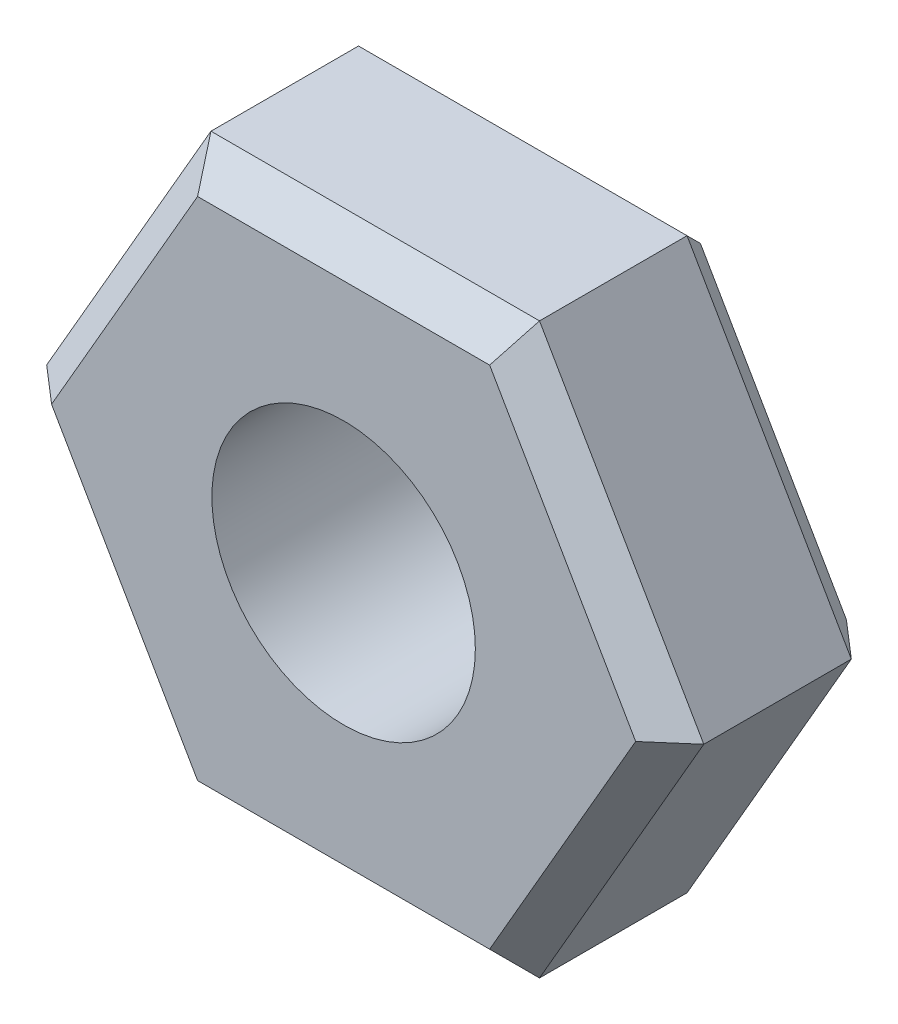
SolidWorks part; units mm, degrees
ref_plane "Front Plane" through (0, 0, 0) normal (0, 0, 1) x (1, 0, 0)
ref_plane "Top Plane" through (0, 0, 0) normal (0, 1, 0) x (1, 0, 0)
ref_plane "Right Plane" through (0, 0, 0) normal (1, 0, 0) x (0, 0, -1)
sketch "Sketch1" plane through (0, 0, 0) normal (0, 0, 1) x (1, 0, 0)
  line L1 (3.1177, 0) -> (1.5588, 2.7)
  line L2 (1.5588, 2.7) -> (-1.5588, 2.7)
  line L3 (-1.5588, 2.7) -> (-3.1177, 0)
  line L4 (-3.1177, 0) -> (-1.5588, -2.7)
  line L5 (-1.5588, -2.7) -> (1.5588, -2.7)
  line L6 (1.5588, -2.7) -> (3.1177, 0)
  circle A0 centre (0, 0) radius 2.7 construction
  circle A1 centre (0, 0) radius 1.25
  dimension "D1" = 5.4
  dimension "D2" = 2.5
extrude "Boss-Extrude1" add sketch "Sketch1" along normal mid plane 2
chamfer "Chamfer1" distance 0.3 angle 45 12 edges at (2.3383, 1.35, -1) (2.3383, -1.35, -1) (0, -2.7, -1) (-2.3383, -1.35, -1) (-2.3383, 1.35, -1) (0, 2.7, -1) (-2.3383, 1.35, 1) (-2.3383, -1.35, 1) (0, -2.7, 1) (2.3383, -1.35, 1) (2.3383, 1.35, 1) (0, 2.7, 1)
